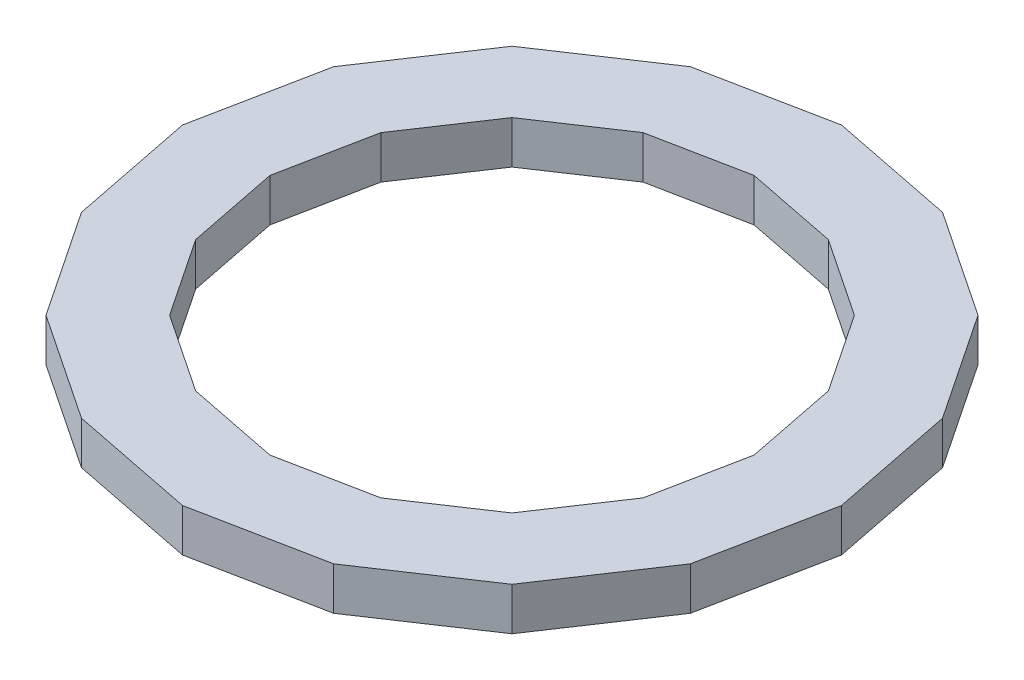
SolidWorks part; units mm, degrees
ref_plane "Front Plane" through (0, 0, 0) normal (0, 0, 1) x (1, 0, 0)
ref_plane "Top Plane" through (0, 0, 0) normal (0, 1, 0) x (1, 0, 0)
ref_plane "Right Plane" through (0, 0, 0) normal (1, 0, 0) x (0, 0, -1)
sketch "Sketch1" plane through (0, 0, 0) normal (0, 1, 0) x (1, 0, 0)
  line L1 (107.6242, 0) -> (99.4318, 41.186)
  line L2 (99.4318, 41.186) -> (76.1018, 76.1018)
  line L3 (76.1018, 76.1018) -> (41.186, 99.4318)
  line L4 (41.186, 99.4318) -> (0, 107.6242)
  line L5 (0, 107.6242) -> (-41.186, 99.4318)
  line L6 (-41.186, 99.4318) -> (-76.1018, 76.1018)
  line L7 (-76.1018, 76.1018) -> (-99.4318, 41.186)
  line L8 (-99.4318, 41.186) -> (-107.6242, 0)
  line L9 (-107.6242, 0) -> (-99.4318, -41.186)
  line L10 (-99.4318, -41.186) -> (-76.1018, -76.1018)
  line L11 (-76.1018, -76.1018) -> (-41.186, -99.4318)
  line L12 (-41.186, -99.4318) -> (0, -107.6242)
  line L13 (0, -107.6242) -> (41.186, -99.4318)
  line L14 (41.186, -99.4318) -> (76.1018, -76.1018)
  line L15 (76.1018, -76.1018) -> (99.4318, -41.186)
  line L16 (99.4318, -41.186) -> (107.6242, 0)
  line L17 (146.4706, 0) -> (135.3212, 56.0519)
  line L18 (135.3212, 56.0519) -> (103.5704, 103.5704)
  line L19 (103.5704, 103.5704) -> (56.0519, 135.3212)
  line L20 (56.0519, 135.3212) -> (0, 146.4706)
  line L21 (0, 146.4706) -> (-56.0519, 135.3212)
  line L22 (-56.0519, 135.3212) -> (-103.5704, 103.5704)
  line L23 (-103.5704, 103.5704) -> (-135.3212, 56.0519)
  line L24 (-135.3212, 56.0519) -> (-146.4706, 0)
  line L25 (-146.4706, 0) -> (-135.3212, -56.0519)
  line L26 (-135.3212, -56.0519) -> (-103.5704, -103.5704)
  line L27 (-103.5704, -103.5704) -> (-56.0519, -135.3212)
  line L28 (-56.0519, -135.3212) -> (0, -146.4706)
  line L29 (0, -146.4706) -> (56.0519, -135.3212)
  line L30 (56.0519, -135.3212) -> (103.5704, -103.5704)
  line L31 (103.5704, -103.5704) -> (135.3212, -56.0519)
  line L32 (135.3212, -56.0519) -> (146.4706, 0)
  circle A1 centre (0, 0) radius 105.5562 construction
  circle A2 centre (0, 0) radius 143.6562 construction
  dimension "D1" = 38.1
  dimension "D2" = 57.15
extrude "Boss-Extrude1" add sketch "Sketch1" along normal blind 19.05
